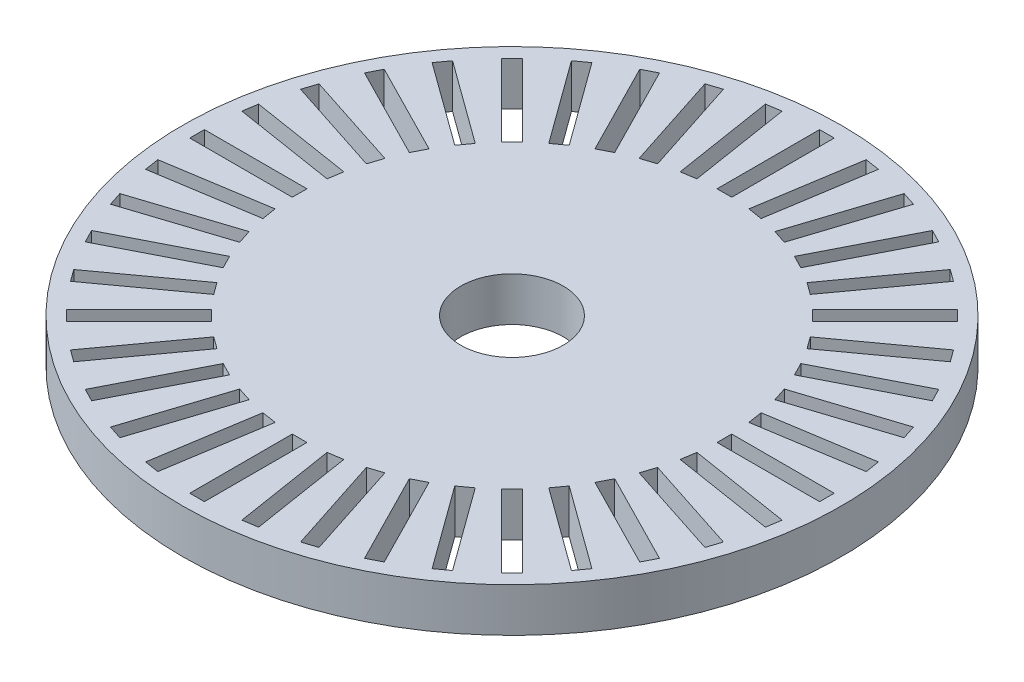
SolidWorks part; units mm, degrees
ref_plane "Alzado" through (0, 0, 0) normal (0, 0, 1) x (1, 0, 0)
ref_plane "Planta" through (0, 0, 0) normal (0, 1, 0) x (1, 0, 0)
ref_plane "Vista lateral" through (0, 0, 0) normal (1, 0, 0) x (0, 0, -1)
sketch "Croquis1" plane through (0, 0, 0) normal (0, 1, 0) x (1, 0, 0)
  line L0 (0, -24.75) -> (0, 24.75) construction
  line L1 (-0.5, 21.5) -> (0.5, 21.5)
  line L2 (-0.5, 21.5) -> (-0.5, 14.5)
  line L3 (-0.5, 14.5) -> (0.5, 14.5)
  line L4 (0.5, 21.5) -> (0.5, 14.5)
  line L5 (-0.5, 21.5) -> (0.5, 14.5) construction
  line L6 (-0.5, 14.5) -> (0.5, 21.5) construction
  line L7 (2.8695, 21.3135) -> (3.8572, 21.1571)
  line L8 (2.8695, 21.3135) -> (1.7745, 14.3997)
  line L9 (3.8572, 21.1571) -> (2.7621, 14.2433)
  line L10 (1.7745, 14.3997) -> (2.7621, 14.2433)
  line L11 (6.1683, 20.6022) -> (7.1194, 20.2932)
  line L12 (6.1683, 20.6022) -> (4.0052, 13.9448)
  line L13 (7.1194, 20.2932) -> (4.9563, 13.6358)
  line L14 (4.0052, 13.9448) -> (4.9563, 13.6358)
  line L15 (9.3153, 19.3836) -> (10.2063, 18.9296)
  line L16 (9.3153, 19.3836) -> (6.1374, 13.1466)
  line L17 (10.2063, 18.9296) -> (7.0284, 12.6926)
  line L18 (6.1374, 13.1466) -> (7.0284, 12.6926)
  line L19 (12.2329, 17.6878) -> (13.0419, 17.1)
  line L20 (12.2329, 17.6878) -> (8.1184, 12.0246)
  line L21 (13.0419, 17.1) -> (8.9274, 11.4369)
  line L22 (8.1184, 12.0246) -> (8.9274, 11.4369)
  line L23 (14.8492, 15.5563) -> (15.5563, 14.8492)
  line L24 (14.8492, 15.5563) -> (9.8995, 10.6066)
  line L25 (15.5563, 14.8492) -> (10.6066, 9.8995)
  line L26 (9.8995, 10.6066) -> (10.6066, 9.8995)
  line L27 (17.1, 13.0419) -> (17.6878, 12.2329)
  line L28 (17.1, 13.0419) -> (11.4369, 8.9274)
  line L29 (17.6878, 12.2329) -> (12.0246, 8.1184)
  line L30 (11.4369, 8.9274) -> (12.0246, 8.1184)
  line L31 (18.9296, 10.2063) -> (19.3836, 9.3153)
  line L32 (18.9296, 10.2063) -> (12.6926, 7.0284)
  line L33 (19.3836, 9.3153) -> (13.1466, 6.1374)
  line L34 (12.6926, 7.0284) -> (13.1466, 6.1374)
  line L35 (20.2932, 7.1194) -> (20.6022, 6.1683)
  line L36 (20.2932, 7.1194) -> (13.6358, 4.9563)
  line L37 (20.6022, 6.1683) -> (13.9448, 4.0052)
  line L38 (13.6358, 4.9563) -> (13.9448, 4.0052)
  line L39 (21.1571, 3.8572) -> (21.3135, 2.8695)
  line L40 (21.1571, 3.8572) -> (14.2433, 2.7621)
  line L41 (21.3135, 2.8695) -> (14.3997, 1.7745)
  line L42 (14.2433, 2.7621) -> (14.3997, 1.7745)
  line L43 (21.5, 0.5) -> (21.5, -0.5)
  line L44 (21.5, 0.5) -> (14.5, 0.5)
  line L45 (21.5, -0.5) -> (14.5, -0.5)
  line L46 (14.5, 0.5) -> (14.5, -0.5)
  line L47 (21.3135, -2.8695) -> (21.1571, -3.8572)
  line L48 (21.3135, -2.8695) -> (14.3997, -1.7745)
  line L49 (21.1571, -3.8572) -> (14.2433, -2.7621)
  line L50 (14.3997, -1.7745) -> (14.2433, -2.7621)
  line L51 (20.6022, -6.1683) -> (20.2932, -7.1194)
  line L52 (20.6022, -6.1683) -> (13.9448, -4.0052)
  line L53 (20.2932, -7.1194) -> (13.6358, -4.9563)
  line L54 (13.9448, -4.0052) -> (13.6358, -4.9563)
  line L55 (19.3836, -9.3153) -> (18.9296, -10.2063)
  line L56 (19.3836, -9.3153) -> (13.1466, -6.1374)
  line L57 (18.9296, -10.2063) -> (12.6926, -7.0284)
  line L58 (13.1466, -6.1374) -> (12.6926, -7.0284)
  line L59 (17.6878, -12.2329) -> (17.1, -13.0419)
  line L60 (17.6878, -12.2329) -> (12.0246, -8.1184)
  line L61 (17.1, -13.0419) -> (11.4369, -8.9274)
  line L62 (12.0246, -8.1184) -> (11.4369, -8.9274)
  line L63 (15.5563, -14.8492) -> (14.8492, -15.5563)
  line L64 (15.5563, -14.8492) -> (10.6066, -9.8995)
  line L65 (14.8492, -15.5563) -> (9.8995, -10.6066)
  line L66 (10.6066, -9.8995) -> (9.8995, -10.6066)
  line L67 (13.0419, -17.1) -> (12.2329, -17.6878)
  line L68 (13.0419, -17.1) -> (8.9274, -11.4369)
  line L69 (12.2329, -17.6878) -> (8.1184, -12.0246)
  line L70 (8.9274, -11.4369) -> (8.1184, -12.0246)
  line L71 (10.2063, -18.9296) -> (9.3153, -19.3836)
  line L72 (10.2063, -18.9296) -> (7.0284, -12.6926)
  line L73 (9.3153, -19.3836) -> (6.1374, -13.1466)
  line L74 (7.0284, -12.6926) -> (6.1374, -13.1466)
  line L75 (7.1194, -20.2932) -> (6.1683, -20.6022)
  line L76 (7.1194, -20.2932) -> (4.9563, -13.6358)
  line L77 (6.1683, -20.6022) -> (4.0052, -13.9448)
  line L78 (4.9563, -13.6358) -> (4.0052, -13.9448)
  line L79 (3.8572, -21.1571) -> (2.8695, -21.3135)
  line L80 (3.8572, -21.1571) -> (2.7621, -14.2433)
  line L81 (2.8695, -21.3135) -> (1.7745, -14.3997)
  line L82 (2.7621, -14.2433) -> (1.7745, -14.3997)
  line L83 (0.5, -21.5) -> (-0.5, -21.5)
  line L84 (0.5, -21.5) -> (0.5, -14.5)
  line L85 (-0.5, -21.5) -> (-0.5, -14.5)
  line L86 (0.5, -14.5) -> (-0.5, -14.5)
  line L87 (-2.8695, -21.3135) -> (-3.8572, -21.1571)
  line L88 (-2.8695, -21.3135) -> (-1.7745, -14.3997)
  line L89 (-3.8572, -21.1571) -> (-2.7621, -14.2433)
  line L90 (-1.7745, -14.3997) -> (-2.7621, -14.2433)
  line L91 (-6.1683, -20.6022) -> (-7.1194, -20.2932)
  line L92 (-6.1683, -20.6022) -> (-4.0052, -13.9448)
  line L93 (-7.1194, -20.2932) -> (-4.9563, -13.6358)
  line L94 (-4.0052, -13.9448) -> (-4.9563, -13.6358)
  line L95 (-9.3153, -19.3836) -> (-10.2063, -18.9296)
  line L96 (-9.3153, -19.3836) -> (-6.1374, -13.1466)
  line L97 (-10.2063, -18.9296) -> (-7.0284, -12.6926)
  line L98 (-6.1374, -13.1466) -> (-7.0284, -12.6926)
  line L99 (-12.2329, -17.6878) -> (-13.0419, -17.1)
  line L100 (-12.2329, -17.6878) -> (-8.1184, -12.0246)
  line L101 (-13.0419, -17.1) -> (-8.9274, -11.4369)
  line L102 (-8.1184, -12.0246) -> (-8.9274, -11.4369)
  line L103 (-14.8492, -15.5563) -> (-15.5563, -14.8492)
  line L104 (-14.8492, -15.5563) -> (-9.8995, -10.6066)
  line L105 (-15.5563, -14.8492) -> (-10.6066, -9.8995)
  line L106 (-9.8995, -10.6066) -> (-10.6066, -9.8995)
  line L107 (-17.1, -13.0419) -> (-17.6878, -12.2329)
  line L108 (-17.1, -13.0419) -> (-11.4369, -8.9274)
  line L109 (-17.6878, -12.2329) -> (-12.0246, -8.1184)
  line L110 (-11.4369, -8.9274) -> (-12.0246, -8.1184)
  line L111 (-18.9296, -10.2063) -> (-19.3836, -9.3153)
  line L112 (-18.9296, -10.2063) -> (-12.6926, -7.0284)
  line L113 (-19.3836, -9.3153) -> (-13.1466, -6.1374)
  line L114 (-12.6926, -7.0284) -> (-13.1466, -6.1374)
  line L115 (-20.2932, -7.1194) -> (-20.6022, -6.1683)
  line L116 (-20.2932, -7.1194) -> (-13.6358, -4.9563)
  line L117 (-20.6022, -6.1683) -> (-13.9448, -4.0052)
  line L118 (-13.6358, -4.9563) -> (-13.9448, -4.0052)
  line L119 (-21.1571, -3.8572) -> (-21.3135, -2.8695)
  line L120 (-21.1571, -3.8572) -> (-14.2433, -2.7621)
  line L121 (-21.3135, -2.8695) -> (-14.3997, -1.7745)
  line L122 (-14.2433, -2.7621) -> (-14.3997, -1.7745)
  line L123 (-21.5, -0.5) -> (-21.5, 0.5)
  line L124 (-21.5, -0.5) -> (-14.5, -0.5)
  line L125 (-21.5, 0.5) -> (-14.5, 0.5)
  line L126 (-14.5, -0.5) -> (-14.5, 0.5)
  line L127 (-21.3135, 2.8695) -> (-21.1571, 3.8572)
  line L128 (-21.3135, 2.8695) -> (-14.3997, 1.7745)
  line L129 (-21.1571, 3.8572) -> (-14.2433, 2.7621)
  line L130 (-14.3997, 1.7745) -> (-14.2433, 2.7621)
  line L131 (-20.6022, 6.1683) -> (-20.2932, 7.1194)
  line L132 (-20.6022, 6.1683) -> (-13.9448, 4.0052)
  line L133 (-20.2932, 7.1194) -> (-13.6358, 4.9563)
  line L134 (-13.9448, 4.0052) -> (-13.6358, 4.9563)
  line L135 (-19.3836, 9.3153) -> (-18.9296, 10.2063)
  line L136 (-19.3836, 9.3153) -> (-13.1466, 6.1374)
  line L137 (-18.9296, 10.2063) -> (-12.6926, 7.0284)
  line L138 (-13.1466, 6.1374) -> (-12.6926, 7.0284)
  line L139 (-17.6878, 12.2329) -> (-17.1, 13.0419)
  line L140 (-17.6878, 12.2329) -> (-12.0246, 8.1184)
  line L141 (-17.1, 13.0419) -> (-11.4369, 8.9274)
  line L142 (-12.0246, 8.1184) -> (-11.4369, 8.9274)
  line L143 (-15.5563, 14.8492) -> (-14.8492, 15.5563)
  line L144 (-15.5563, 14.8492) -> (-10.6066, 9.8995)
  line L145 (-14.8492, 15.5563) -> (-9.8995, 10.6066)
  line L146 (-10.6066, 9.8995) -> (-9.8995, 10.6066)
  line L147 (-13.0419, 17.1) -> (-12.2329, 17.6878)
  line L148 (-13.0419, 17.1) -> (-8.9274, 11.4369)
  line L149 (-12.2329, 17.6878) -> (-8.1184, 12.0246)
  line L150 (-8.9274, 11.4369) -> (-8.1184, 12.0246)
  line L151 (-10.2063, 18.9296) -> (-9.3153, 19.3836)
  line L152 (-10.2063, 18.9296) -> (-7.0284, 12.6926)
  line L153 (-9.3153, 19.3836) -> (-6.1374, 13.1466)
  line L154 (-7.0284, 12.6926) -> (-6.1374, 13.1466)
  line L155 (-7.1194, 20.2932) -> (-6.1683, 20.6022)
  line L156 (-7.1194, 20.2932) -> (-4.9563, 13.6358)
  line L157 (-6.1683, 20.6022) -> (-4.0052, 13.9448)
  line L158 (-4.9563, 13.6358) -> (-4.0052, 13.9448)
  line L159 (-3.8572, 21.1571) -> (-2.8695, 21.3135)
  line L160 (-3.8572, 21.1571) -> (-2.7621, 14.2433)
  line L161 (-2.8695, 21.3135) -> (-1.7745, 14.3997)
  line L162 (-2.7621, 14.2433) -> (-1.7745, 14.3997)
  circle A0 centre (0, 0) radius 22.5
  circle A1 centre (0, 0) radius 3.5
  circle A2 centre (0, 0) radius 22.5
  circle A3 centre (0, 0) radius 22.5
  circle A4 centre (0, 0) radius 22.5
  circle A5 centre (0, 0) radius 22.5
  circle A6 centre (0, 0) radius 22.5
  circle A7 centre (0, 0) radius 22.5
  circle A8 centre (0, 0) radius 22.5
  circle A9 centre (0, 0) radius 22.5
  circle A10 centre (0, 0) radius 22.5
  circle A11 centre (0, 0) radius 22.5
  circle A12 centre (0, 0) radius 22.5
  circle A13 centre (0, 0) radius 22.5
  circle A14 centre (0, 0) radius 22.5
  circle A15 centre (0, 0) radius 22.5
  circle A16 centre (0, 0) radius 22.5
  circle A17 centre (0, 0) radius 22.5
  circle A18 centre (0, 0) radius 22.5
  circle A19 centre (0, 0) radius 22.5
  circle A20 centre (0, 0) radius 22.5
  circle A21 centre (0, 0) radius 22.5
  circle A22 centre (0, 0) radius 22.5
  circle A23 centre (0, 0) radius 22.5
  circle A24 centre (0, 0) radius 22.5
  circle A25 centre (0, 0) radius 22.5
  circle A26 centre (0, 0) radius 22.5
  circle A27 centre (0, 0) radius 22.5
  circle A28 centre (0, 0) radius 22.5
  circle A29 centre (0, 0) radius 22.5
  circle A30 centre (0, 0) radius 22.5
  circle A31 centre (0, 0) radius 22.5
  circle A32 centre (0, 0) radius 22.5
  circle A33 centre (0, 0) radius 22.5
  circle A34 centre (0, 0) radius 22.5
  circle A35 centre (0, 0) radius 22.5
  circle A36 centre (0, 0) radius 22.5
  circle A37 centre (0, 0) radius 22.5
  circle A38 centre (0, 0) radius 22.5
  circle A39 centre (0, 0) radius 22.5
  circle A40 centre (0, 0) radius 22.5
  point P4 (0, 18)
  point P209 (0, 0)
  dimension "D1" = 45
  dimension "D2" = 7
  dimension "D4" = 18
  dimension "D3" = 7
  dimension "D5" = 1
  dimension "D6" = 40
extrude "Saliente-Extruir1" add sketch "Croquis1" along normal blind 3 contours A0 A1 L1 L4 L3 L2 L10 L8 L7 L9 L14 L12 L11 L13 L18 L16 L15 L17 L22 L20 L19 L21 L26 L24 L23 L25 L30 L28 L27 L29 L34 L32 L31 L33 L38 L36 L35 L37 L42 L40
